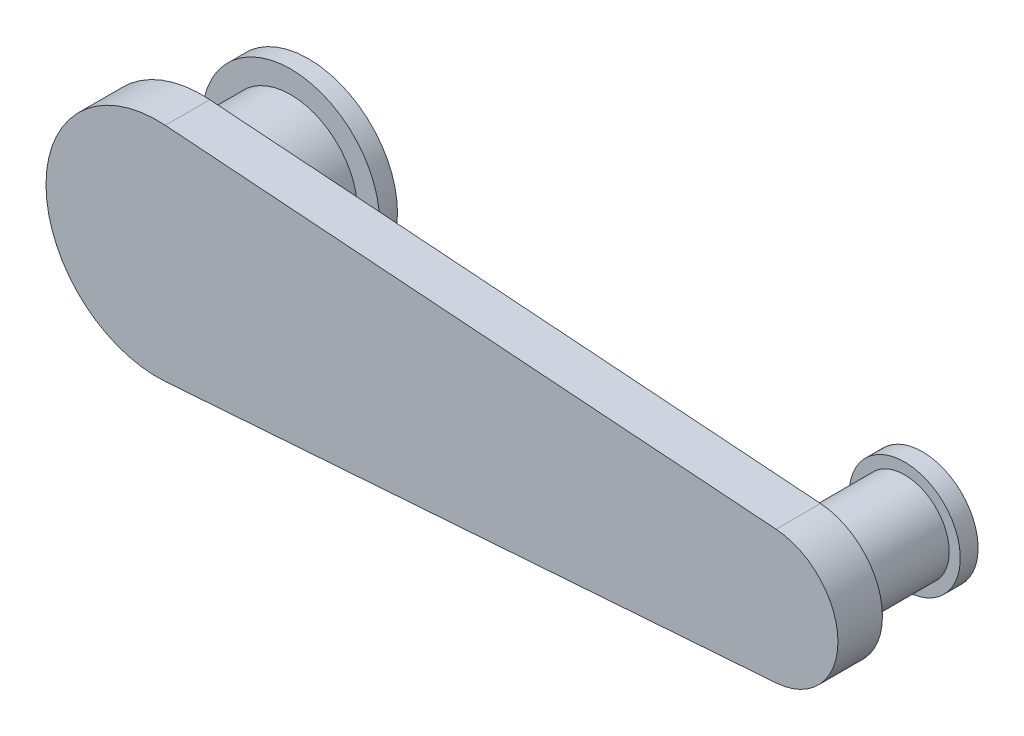
SolidWorks part; units mm, degrees
ref_plane "Front Plane" through (0, 0, 0) normal (0, 0, 1) x (1, 0, 0)
ref_plane "Top Plane" through (0, 0, 0) normal (0, 1, 0) x (1, 0, 0)
ref_plane "Right Plane" through (0, 0, 0) normal (1, 0, 0) x (0, 0, -1)
sketch "Sketch1" plane through (0, 0, 0) normal (0, 0, 1) x (1, 0, 0)
  line L0 (-280.942, 124.6714) -> (405.4348, 74.8028)
  line L1 (-486.483, 0) -> (508.7987, 0) construction
  line L2 (-280.942, -124.6714) -> (405.4348, -74.8028)
  arc A0 (405.4348, 74.8028) -> (405.4348, -74.8028) centre (400, 0) cw
  arc A1 (-280.942, 124.6714) -> (-280.942, -124.6714) centre (-290, 0) ccw
  circle A2 centre (-290, 0) radius 75
  circle A3 centre (400, 0) radius 50
  dimension "D1" = 150
  dimension "D2" = 125
  dimension "D4" = 100
  dimension "D5" = 75
  dimension "D3" = 290
  dimension "D6" = 400
extrude "Boss-Extrude1" add sketch "Sketch1" along normal mid plane 50 contours A2 L1 | L1 A2 | A1 L1 A2 A3 A0 L0 | L1 A1 L2 A0 A3 A2 | L1 A3 | A3 L1
sketch "Sketch2" plane through (0, 0, -25) normal (0, 0, -1) x (-1, 0, 0)
  circle A0 centre (290, 0) radius 75
  circle A1 centre (-400, 0) radius 50
  dimension "D1" = 100
  dimension "D2" = 150
extrude "Boss-Extrude2" add sketch "Sketch2" along normal blind 100
sketch "Sketch3" plane through (0, 0, -125) normal (0, 0, -1) x (-1, 0, 0)
  circle A0 centre (-400, 0) radius 62.5
  circle A1 centre (290, 0) radius 100
  dimension "D1" = 125
  dimension "D2" = 200
extrude "Boss-Extrude3" add sketch "Sketch3" along normal blind 20
